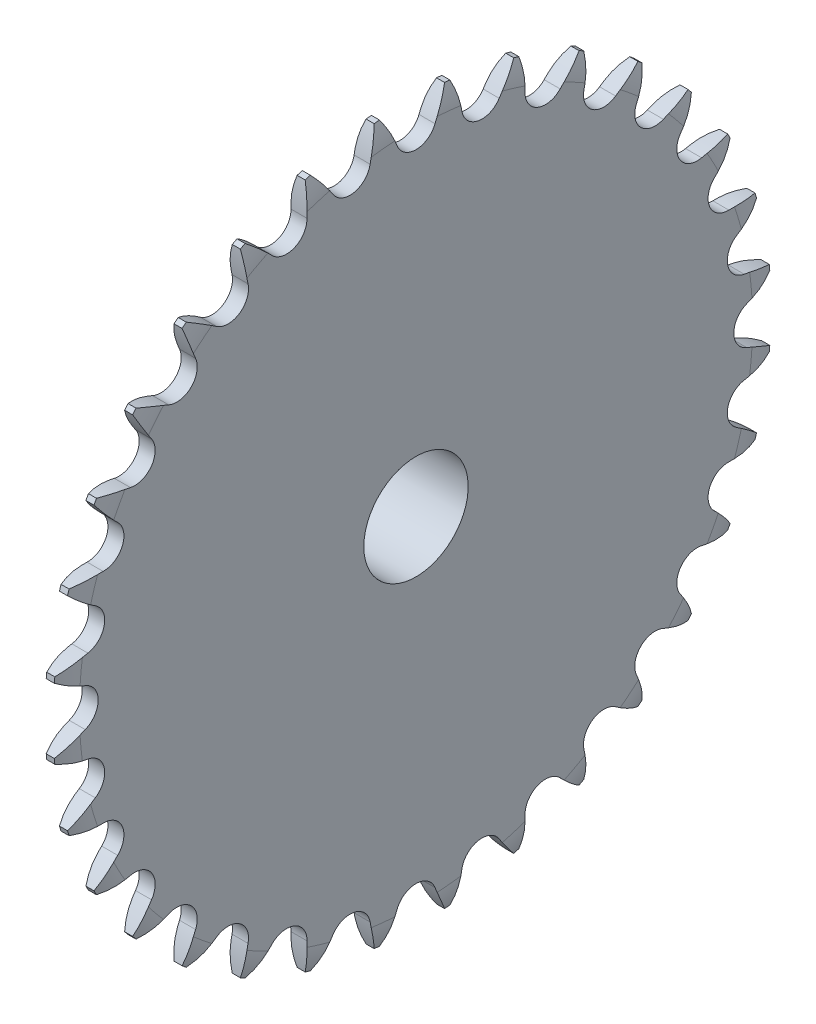
SolidWorks part; units mm, degrees
ref_plane "Plane1" through (0, 0, 0) normal (0, 0, 1) x (1, 0, 0)
ref_plane "Plane2" through (0, 0, 0) normal (0, 1, 0) x (1, 0, 0)
ref_plane "Plane3" through (0, 0, 0) normal (1, 0, 0) x (0, 0, -1)
sketch "Clipboard" plane through (0, 0, 0) normal (0, 1, 0) x (1, 0, 0)
  line L0 (0, 0) -> (10.7702, -6.73)
  line L1 (-15, 0) -> (100, 0) construction
  line L2 (0, 0) -> (-0.5049, 0.5707)
  line L3 (0, 0) -> (-11.863, 4.5341)
  line L4 (0, 0) -> (2.6289, 1.6427)
  line L5 (0, 0) -> (-20.613, -7.688)
  line L6 (0, 0) -> (-2.5441, -1.7165)
  line L7 (-0.5049, 0.5707) -> (17.9462, 12.553)
  line L8 (-76.2, 38.1) -> (-73.4, 38.1)
  line L9 (-73.2427, 39.6204) -> (-72.6435, 39.6525)
  line L10 (-73.1375, 10.4807) -> (-66.1375, 10.4807)
  circle A0 centre (0, 0) radius 3.875
  circle A1 centre (0, 0) radius 20
  circle A2 centre (0, 0) radius 20
  dimension "Dr" = 7.75
  dimension "MHD" = 40
  dimension "Hub_dia" = 40
  dimension "Num_teeth" = 32
  dimension "Pitch" = 12.7
  dimension "Width" = 3.1
  dimension "Side_relief" = 0.762
  dimension "Side_radius" = 12.7
  dimension "Overall_len" = 22
  dimension "Show_teeth" = 32
  dimension "Thickness" = 3.069
  dimension "OAL" = 22.0005
  dimension "T_dim" = 2.8
  dimension "Fillet_rad" = 0.6
  dimension "Face_width" = 3.069
  dimension "Num_strands" = 1
  dimension "Transv_pitch" = 7
  dimension "Plate_wid" = 9.91
sketch "BasProSke" plane through (0, 0, 0) normal (0, 1, 0) x (1, 0, 0)
  line L0 (-10, 0) -> (60, 0) construction
  line L1 (0, 0) -> (0, 64.5142)
  line L2 (0, 0) -> (3.069, 0)
  line L3 (3.069, 0) -> (3.069, 64.5142)
  line L4 (2.307, 68.8471) -> (0.762, 68.8471)
  arc A0 (0, 64.5142) -> (0.762, 68.8471) centre (12.7, 64.5142) cw
  arc A1 (3.069, 64.5142) -> (2.307, 68.8471) centre (-9.631, 64.5142) ccw
  dimension "Thickness" = 3.069
  dimension "D1" = 12.7
  dimension "G1" = 0.762
  dimension "G2" = 0.762
  dimension "Diameter" = 137.6942
revolve "Base-Revolve" add sketch "BasProSke" angle 360 about L0
sketch "TooCutSke" plane through (0, 0, 0) normal (1, 0, 0) x (0, 0, -1)
  line L0 (0, 64.8233) -> (3.6438, 63.3949) construction
  line L1 (0, 0) -> (0, 107) construction
  line L2 (0, 64.8233) -> (-10, 64.8233) construction
  line L3 (0, 64.8233) -> (-3.6438, 63.3949) construction
  arc A0 (3.6438, 63.3949) -> (6.5393, 69.0381) centre (33.0825, 51.8543) cw
  arc A1 (3.6438, 63.3949) -> (-3.6438, 63.3949) centre (0, 64.8233) cw
  arc A2 (-3.6438, 63.3949) -> (-6.5393, 69.0381) centre (-33.0825, 51.8543) ccw
  arc A3 (6.5393, 69.0381) -> (-6.5393, 69.0381) centre (0, 0) ccw
  dimension "R1" = 3.9137
  dimension "R2" = 31.62
  dimension "Overcut" = 69.3471
  dimension "Seat_radius" = 64.8233
  dimension "X" = 137.188
extrude "ToothCut" cut sketch "TooCutSke" along normal through all
pattern_circular "TeethCuts" count 32 every 11.25 about axis through (-10, 0, 0) along (1, 0, 0) of "ToothCut"
sketch "HubNeaOneSke" plane through (0, 0, 0) normal (-1, 0, 0) x (0, 0, 1)
  circle A0 centre (0, 0) radius 20
  dimension "Diameter" = 40
extrude "HubNearOne" add sketch "HubNeaOneSke" along normal blind 22
fillet "HubNearOneFillet" radius 0.6 1 edges at (0, 0, -20)
sketch "HubNeaBotSke" plane through (0, 0, 0) normal (-1, 0, 0) x (0, 0, 1)
  circle A0 centre (0, 0) radius 20
  dimension "Diameter" = 40
extrude "HubNearBoth" [suppressed] add sketch "HubNeaBotSke" along normal blind 9.4657
fillet "HubNearBothFillet" [suppressed] radius 0.6
ref_plane "FarPln" through (3.069, 0, 0) normal (1, 0, 0) x (0, 0, -1)
sketch "HubFarSke" plane through (3.069, 0, 0) normal (1, 0, 0) x (0, 0, -1)
  circle A0 centre (0, 0) radius 20
  dimension "Diameter" = 40
extrude "HubFar" [suppressed] add sketch "HubFarSke" along normal blind 9.4657
fillet "HubFarFillet" [suppressed] radius 0.6
sketch "BorSke" plane through (0, 0, 0) normal (1, 0, 0) x (0, 0, -1)
  circle A0 centre (0, 0) radius 10
  dimension "Diameter" = 20
extrude "Bore" cut sketch "BorSke" along normal mid plane 44.001
sketch "KeySke" plane through (0, 0, 0) normal (1, 0, 0) x (0, 0, -1)
  line L0 (-3, 0) -> (-3, 12.8)
  line L1 (-3, 12.8) -> (3, 12.8)
  line L2 (3, 12.8) -> (3, 0)
  line L3 (0, 0) -> (0, 34) construction
  line L4 (-3, 0) -> (3, 0)
  dimension "Offset" = 12.8
  dimension "Width" = 6
extrude "Keyway" [suppressed] cut sketch "KeySke" along normal mid plane 44.001
pattern_circular "Keyway2" [suppressed] count 2 every 90 about axis through (-10, 0, 0) along (1, 0, 0)
sketch "Эскиз1" plane through (0, 0, 0) normal (0, 1, 0) x (1, 0, 0)
  line L2 (-22, 20) -> (-22, -20) construction
  line L4 (0, 3.6438) -> (0, -3.6438) construction
  circle A0 centre (-13, 0) radius 4
  point P9 (0, 0)
  dimension "D1" = 8
  dimension "D2" = 5
extrude "Вырез-Вытянуть1" cut sketch "Эскиз1" against normal up to next
equation "' \"Pitch@Clipboard\" = 12.7"
equation "' \"Num_strands@Clipboard\" = 1"
equation "' \"Num_teeth@Clipboard\" = 9"
equation "' \"Hub_dia@Clipboard\" = 50"
equation "' \"Overall_len@Clipboard\" = 3"
equation "' \"Diameter@BorSke\" = 12"
equation "' \"T_dim@Clipboard\" = 1"
equation "' \"Width@KeySke\" = 2"
equation "' \"Dr@Clipboard\" = 8.51"
equation "' \"Face_width@Clipboard\" = 7.2"
equation "' \"Side_radius@Clipboard\" = 12.7"
equation "' \"Side_relief@Clipboard\" = 1.27"
equation "' \"Transv_pitch@Clipboard\" = 13.92"
equation "' \"Show_teeth@Clipboard\" = 9"
equation "' \"Fillet_rad@Clipboard\" = 0.6"
equation "' \"Plate_wid@Clipboard\" = 11.8"
equation "\"Num_teeth@Clipboard\" = int( \"Num_teeth@Clipboard\" )"
equation "\"Num_teeth@Clipboard\" = ((sgn( \"Num_teeth@Clipboard\" - 5.0)+1)*( \"Num_teeth@Clipboard\" - 5.0))/2 +5.0"
equation "\"Num_teeth@Clipboard\" = ((sgn( \"Num_teeth@Clipboard\" - 200.0)-1)*( \"Num_teeth@Clipboard\" - 200.0))/-2 +200.0"
equation "\"MHD@Clipboard\" = \"Pitch@Clipboard\" * (1.0 / tan(3.14159265 / \"Num_teeth@Clipboard\" )) - 1.04 * \"Plate_wid@Clipboard\" - 0.76"
equation "\"Thickness@Clipboard\"  = \"Face_width@Clipboard\" + (\"Num_strands@Clipboard\" - 1) * \"Transv_pitch@Clipboard\""
equation "\"OAL@Clipboard\" = \"Thickness@Clipboard\" + 2 * \"Fillet_rad@Clipboard\" + 1"
equation "\"MHD@Clipboard\" = ((sgn( \"MHD@Clipboard\" - \"Hub_dia@Clipboard\" )-1)*( \"MHD@Clipboard\" - \"Hub_dia@Clipboard\" ))/-2+ \"Hub_dia@Clipboard\""
equation "\"OAL@Clipboard\" = ((sgn( \"OAL@Clipboard\" - \"Overall_len@Clipboard\" )+1)*( \"OAL@Clipboard\" - \"Overall_len@Clipboard\" ))/2 + \"Overall_len@Clipboard\" + 0.0005"
equation "\"Num_teeth@TeethCuts\" = int( \"Show_teeth@Clipboard\" ) + 1"
equation "\"Num_teeth@TeethCuts\" = ((sgn( \"Num_teeth@TeethCuts\" - \"Num_teeth@Clipboard\" )-1)*( \"Num_teeth@TeethCuts\" - \"Num_teeth@Clipboard\" ))/-2+ \"Num_teeth@Clipboard\""
equation "\"Num_teeth@TeethCuts\" = ((sgn( \"Num_teeth@TeethCuts\" - 2.0)+1)*( \"Num_teeth@TeethCuts\" - 2.0))/2 +2.0"
equation "\"Angle@TeethCuts\" = 360.0 / \"Num_teeth@Clipboard\""
equation "\"Seat_radius@TooCutSke\" = ( \"Pitch@Clipboard\" / 2.0) / sin(3.14159265 / \"Num_teeth@Clipboard\" ) - \"Dr@Clipboard\" / 2.0 + \"Dr@Clipboard\" * 0.505"
equation "\"R1@TooCutSke\"  = \"Dr@Clipboard\" * 0.505"
equation "\"X@TooCutSke\" = 140.0 - (90.0 / \"Num_teeth@Clipboard\")"
equation "\"R2@TooCutSke\" = 0.12 * \"Dr@Clipboard\" * ( \"Num_teeth@Clipboard\" + 2.0)"
equation "\"Overcut@TooCutSke\" = 0.5 + 0.625 * \"Pitch@Clipboard\" - 0.5 * \"Dr@Clipboard\"  +  \"Pitch@Clipboard\" / 2.0 / sin(3.14159265 / \"Num_teeth@Clipboard\" )"
equation "\"Diameter@BasProSke\" = 2.0 * ( 0.625 * \"Pitch@Clipboard\" - 0.5 * \"Dr@Clipboard\"  +  \"Pitch@Clipboard\" / 2.0 / sin(3.14159265 / \"Num_teeth@Clipboard\" ))"
equation "\"Thickness@BasProSke\"  = \"Thickness@Clipboard\""
equation "\"G1@BasProSke\" =  \"Side_relief@Clipboard\""
equation "\"G2@BasProSke\" =  \"Side_relief@Clipboard\""
equation "\"D1@BasProSke\" =  \"Side_radius@Clipboard\""
equation "\"Diameter@HubNeaOneSke\" = \"MHD@Clipboard\""
equation "\"Diameter@HubNeaBotSke\" = \"MHD@Clipboard\""
equation "\"Length@HubNearBoth\" = ( \"OAL@Clipboard\" - \"Thickness@BasProSke\" ) / 2.0"
equation "\"D1@HubNearOneFillet\" = \"Fillet_rad@Clipboard\""
equation "\"D1@HubNearBothFillet\" = \"Fillet_rad@Clipboard\""
equation "\"Thickness@FarPln\" = \"Thickness@BasProSke\""
equation "\"Diameter@HubFarSke\" = \"MHD@Clipboard\""
equation "\"Length@HubFar\" = ( \"OAL@Clipboard\" - \"Thickness@BasProSke\" ) / 2.0"
equation "\"D1@HubFarFillet\" = \"Fillet_rad@Clipboard\""
equation "\"D1@Bore\" = \"OAL@Clipboard\" * 2.0"
equation "\"D1@Keyway\" = \"OAL@Clipboard\" * 2.0"
equation "\"Offset@KeySke\" = \"T_dim@Clipboard\" + \"Diameter@BorSke\" / 2.0"
